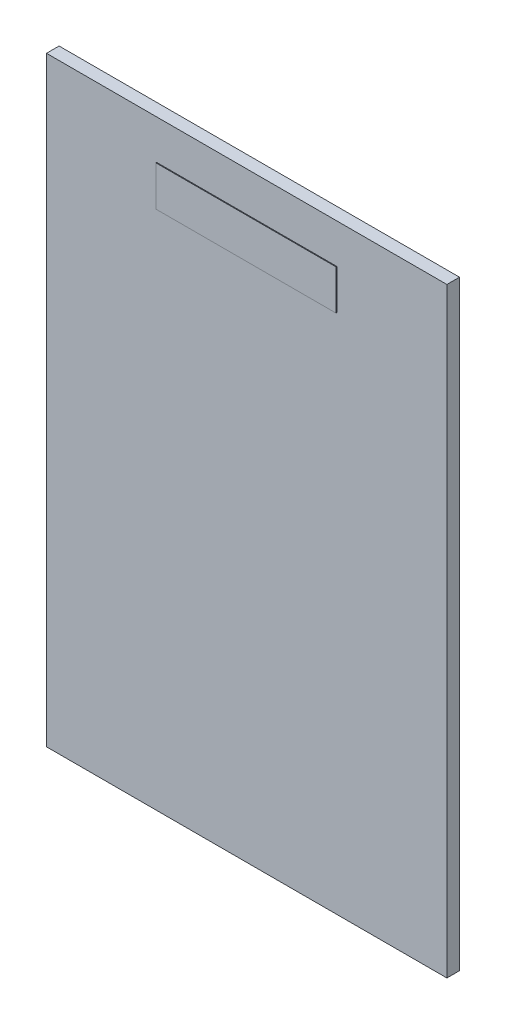
SolidWorks part; units mm, degrees
ref_plane "Front Plane" through (0, 0, 0) normal (0, 0, 1) x (1, 0, 0)
ref_plane "Top Plane" through (0, 0, 0) normal (0, 1, 0) x (1, 0, 0)
ref_plane "Right Plane" through (0, 0, 0) normal (1, 0, 0) x (0, 0, -1)
sketch "Sketch1" plane through (0, 0, 0) normal (0, 0, 1) x (1, 0, 0)
  line L1 (25.4, -38.1) -> (-25.4, -38.1)
  line L2 (25.4, -38.1) -> (25.4, 38.1)
  line L3 (25.4, 38.1) -> (-25.4, 38.1)
  line L4 (-25.4, -38.1) -> (-25.4, 38.1)
  line L5 (25.4, -38.1) -> (-25.4, 38.1) construction
  line L6 (25.4, 38.1) -> (-25.4, -38.1) construction
  point P0 (0, 0)
  dimension "D1" = 50.8
  dimension "D2" = 76.2
extrude "Boss-Extrude1" add sketch "Sketch1" along normal blind 1.6
sketch "Sketch5" plane through (0, 0, 0) normal (0, 0, 1) x (1, 0, 0)
  line L0 (-25.3238, 38.0215) -> (25.4762, 38.0215) construction
  dimension "D1" = 50.8
sketch "Sketch3" plane through (0, 0, 1.6) normal (0, 0, 1) x (1, 0, 0)
  line L0 (25.4, 38.1) -> (-25.4, 38.1) construction
  line L1 (-11.43, 28.02) -> (11.43, 28.02)
  line L2 (-11.43, 28.02) -> (-11.43, 33.1)
  line L3 (-11.43, 33.1) -> (11.43, 33.1)
  line L4 (11.43, 28.02) -> (11.43, 33.1)
  line L5 (-11.43, 28.02) -> (11.43, 33.1) construction
  line L6 (-11.43, 33.1) -> (11.43, 28.02) construction
  point P0 (0, 30.56)
  point P5 (0, 0)
  dimension "D1" = 22.86
  dimension "D2" = 5.08
  dimension "D3" = 5
extrude "Boss-Extrude2" add sketch "Sketch3" along normal blind 0.1
sketch "Sketch6" plane through (0, 0, 0) normal (0, 0, -1) x (-1, 0, 0)
  line L1 (14.2786, -19.2783) -> (-14.2786, -19.2783)
  line L2 (14.2786, -19.2783) -> (14.2786, 22.7352)
  line L3 (14.2786, 22.7352) -> (-14.2786, 22.7352)
  line L4 (-14.2786, -19.2783) -> (-14.2786, 22.7352)
  line L5 (14.2786, -19.2783) -> (-14.2786, 22.7352) construction
  line L6 (14.2786, 22.7352) -> (-14.2786, -19.2783) construction
  point P0 (0, 1.7285)
  point P5 (0, 10.8316)
  point P6 (14.4278, 22.1827)
  point P7 (-14.1293, 22.1827)
  point P8 (0, 1.7285)
  dimension "D1" = 50.8
extrude "Boss-Extrude3" add sketch "Sketch6" along normal blind 2
